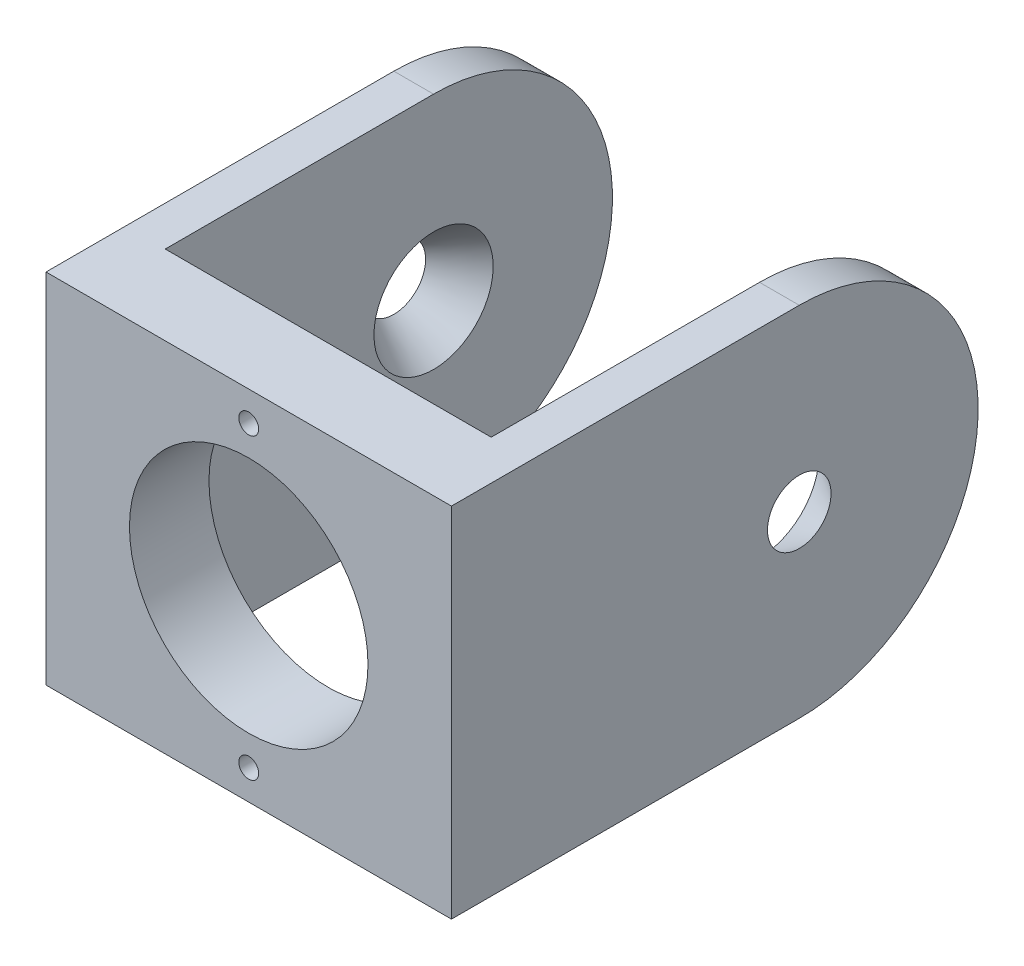
SolidWorks part; units mm, degrees
ref_plane "Front Plane" through (0, 0, 0) normal (0, 0, 1) x (1, 0, 0)
ref_plane "Top Plane" through (0, 0, 0) normal (0, 1, 0) x (1, 0, 0)
ref_plane "Right Plane" through (0, 0, 0) normal (1, 0, 0) x (0, 0, -1)
sketch "Sketch1" plane through (0, 0, 0) normal (0, 0, 1) x (1, 0, 0)
  line L1 (-6, -7) -> (6, -7)
  line L2 (-6, -7) -> (-6, 7)
  line L3 (-6, 7) -> (6, 7)
  line L4 (6, -7) -> (6, 7)
  line L5 (-6, -7) -> (6, 7) construction
  line L6 (-6, 7) -> (6, -7) construction
  point P0 (0, 0)
  dimension "D1" = 12
  dimension "D2" = 14
extrude "Extrude-Thin1" add sketch "Sketch1" along normal mid plane 4 thin
sketch "Sketch2" plane through (8, 0, 0) normal (1, 0, 0) x (0, 0, -1)
  line L0 (-2, 9) -> (2, 9) construction
  line L1 (0, 9) -> (-17.5, 9)
  line L2 (0, 9) -> (0, -9)
  line L3 (0, -9) -> (-17.5, -9)
  line L6 (-2, -9) -> (2, -9) construction
  line L7 (0, 55) -> (0, -55) construction
  line L8 (55, 0) -> (-55, 0) construction
  arc A0 (-17.5, 9) -> (-17.5, -9) centre (-17.5, 0) ccw
  dimension "D1" = 17.5
extrude "Boss-Extrude1" [suppressed] add sketch "Sketch2" against normal up to surface (2 mm away)
sketch "Sketch3" [suppressed] plane through (8, 0, 0) normal (1, 0, 0) x (0, 0, -1)
  line L0 (11.22, 0) -> (-11.22, 0) construction
  circle A0 centre (-17.5, 0) radius 3
  arc A1 (-17.5, 9) -> (-17.5, -9) centre (-17.5, 0) ccw construction
  dimension "D1" = 6
extrude "Boss-Extrude2" [suppressed] add sketch "Sketch3" along normal blind 2 draft 35
sketch "Sketch4" plane through (8, 0, 0) normal (1, 0, 0) x (0, 0, -1)
  line L1 (-2, 9) -> (15.5, 9)
  line L2 (-2, 9) -> (-2, -9)
  line L3 (-2, -9) -> (15.5, -9)
  line L5 (-2, 9) -> (2, 9) construction
  line L6 (-2, -9) -> (2, -9) construction
  line L7 (11.22, 0) -> (-11.22, 0) construction
  line L8 (-2, -9) -> (-2, 9) construction
  arc A0 (15.5, 9) -> (15.5, -9) centre (15.5, 0) cw
  dimension "D1" = 17.5
extrude "Boss-Extrude3" add sketch "Sketch4" along normal blind 2.2
sketch "Sketch10" plane through (0, 9, 0) normal (0, 1, 0) x (1, 0, 0)
  line L1 (8, 2) -> (8.2, 2)
  line L2 (8, 2) -> (8, 29.5315)
  line L3 (8, 29.5315) -> (8.2, 29.5315)
  line L4 (8.2, 2) -> (8.2, 29.5315)
  dimension "D1" = 0.2
extrude "Cut-Extrude4" cut sketch "Sketch10" against normal up to next
sketch "Sketch5" plane through (8.2, 0, 0) normal (-1, 0, 0) x (0, 0, 1)
  circle A0 centre (-15.5, 0) radius 3
  dimension "D1" = 6
extrude "Cut-Extrude1" cut sketch "Sketch5" against normal up to next (2 mm away) draft 35
mirror "Mirror3" about plane through (0, 0, 0) normal (1, 0, 0) of "Cut-Extrude4", "Boss-Extrude1", "Cut-Extrude1", "Boss-Extrude2", "Extrude-Thin1", "Boss-Extrude3"
sketch "Sketch13" [suppressed] plane through (0, 0, 2) normal (0, 0, 1) x (1, 0, 0)
  line L0 (6, 9) -> (6, -9) construction
  line L1 (-6, 7) -> (6, 7)
  line L2 (-6, 7) -> (-6, 6)
  line L3 (-6, 6) -> (6, 6)
  line L4 (6, 7) -> (6, 6)
  dimension "D1" = 1
extrude "Boss-Extrude4" [suppressed] add sketch "Sketch13" against normal up to surface (4 mm away)
mirror "Mirror5" [suppressed] about plane through (0, 0, 0) normal (0, 1, 0)
sketch "Sketch11" [suppressed] plane through (0, 0, 4) normal (0, 0, 1) x (1, 0, 0)
  line L0 (-4.5, 9) -> (-4.5, 6) construction
  line L1 (-6, 6) -> (6, 6) construction
  line L2 (6, 9) -> (-6, 9) construction
  line L3 (0, -9.9) -> (0, 9.9) construction
  circle A0 centre (-4.5, 7.5) radius 0.5
  dimension "D2" = 1
  dimension "D1" = 4.5
extrude "Cut-Extrude5" [suppressed] cut sketch "Sketch11" against normal up to next
mirror "Mirror4" [suppressed] about plane through (0, 0, 0) normal (0, 1, 0)
sketch "Sketch14" plane through (0, -7, 0) normal (0, 1, 0) x (1, 0, 0)
  line L4 (6, 2) -> (-6, 2)
  line L5 (-6, 2) -> (-6, -2)
  line L6 (-6, -2) -> (6, -2)
  line L7 (6, -2) -> (6, 2)
  line L8 (6, 2) -> (-6, 2)
  line L9 (-6, 2) -> (-6, -2)
  line L10 (-6, -2) -> (6, -2)
  line L11 (6, -2) -> (6, 2)
  dimension "D1" = 0
extrude "Boss-Extrude5" add sketch "Sketch14" along normal up to surface (14 mm away) up to face at (0, 7, 0)
sketch "Sketch15" plane through (0, 0, -2) normal (0, 0, -1) x (-1, 0, 0)
  circle A0 centre (0, 0) radius 6
  dimension "D1" = 12
extrude "Cut-Extrude6" cut sketch "Sketch15" against normal up to next
sketch "Sketch19" plane through (0, 0, -2) normal (0, 0, -1) x (-1, 0, 0)
  line L0 (-8.2, 6) -> (8.2, 6) construction
  line L1 (8.2, -9) -> (8.2, 9) construction
  line L2 (-8.2, -9) -> (-8.2, 9) construction
  line L3 (0, 9) -> (0, 6) construction
  line L4 (-8.2, 9) -> (8.2, 9) construction
  circle A0 centre (0, 0) radius 6 construction
  circle A1 centre (0, 7.5) radius 0.5
  point P2 (0, 6)
  dimension "D2" = 1
extrude "Cut-Extrude8" cut sketch "Sketch19" against normal up to next
mirror "Mirror8" about plane through (0, 0, 0) normal (0, 1, 0) of "Cut-Extrude8" second plane through (0, 0, 0) second plane normal (1, 0, 0)
